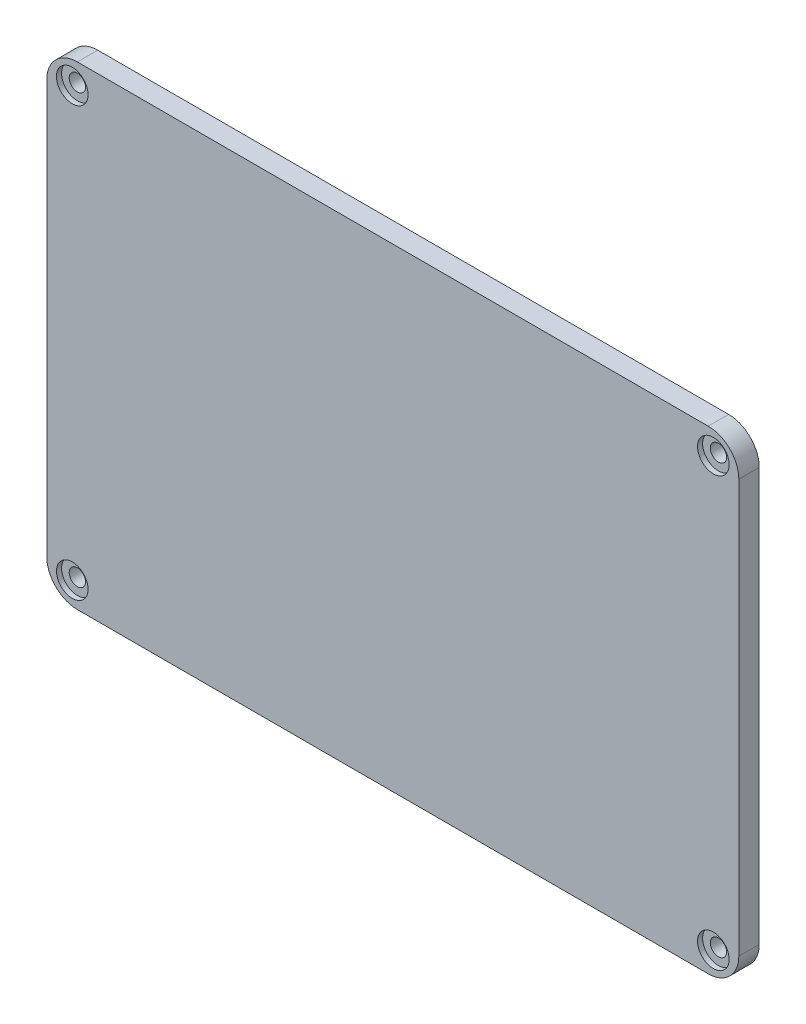
SolidWorks part; units mm, degrees
ref_plane "Front Plane" through (0, 0, 0) normal (0, 0, 1) x (1, 0, 0)
ref_plane "Top Plane" through (0, 0, 0) normal (0, 1, 0) x (1, 0, 0)
ref_plane "Right Plane" through (0, 0, 0) normal (1, 0, 0) x (0, 0, -1)
sketch "Sketch1" plane through (0, 0, 0) normal (0, 0, 1) x (1, 0, 0)
  line L25 (-12.2044, -60.1102) -> (-12.2044, -141.1102)
  line L26 (-6.2044, -147.1102) -> (117.4956, -147.1102)
  line L27 (123.4956, -141.1102) -> (123.4956, -60.1102)
  line L28 (117.4956, -54.1102) -> (-6.2044, -54.1102)
  line L45 (-12.2044, -60.1102) -> (-12.2044, -141.1102)
  line L46 (-6.2044, -147.1102) -> (117.4956, -147.1102)
  line L47 (123.4956, -141.1102) -> (123.4956, -60.1102)
  line L48 (117.4956, -54.1102) -> (-6.2044, -54.1102)
  circle A0 centre (-7.2044, -58.6102) radius 1.6
  circle A1 centre (118.4956, -58.6102) radius 1.6
  circle A2 centre (118.4956, -142.6102) radius 1.6
  circle A3 centre (-7.2044, -142.6102) radius 1.6
  arc A4 (-12.2044, -141.1102) -> (-6.2044, -147.1102) centre (-6.2044, -141.1102) ccw
  arc A5 (117.4956, -147.1102) -> (123.4956, -141.1102) centre (117.4956, -141.1102) ccw
  arc A6 (123.4956, -60.1102) -> (117.4956, -54.1102) centre (117.4956, -60.1102) ccw
  arc A7 (-6.2044, -54.1102) -> (-12.2044, -60.1102) centre (-6.2044, -60.1102) ccw
  arc A8 (-12.2044, -141.1102) -> (-6.2044, -147.1102) centre (-6.2044, -141.1102) ccw
  arc A9 (117.4956, -147.1102) -> (123.4956, -141.1102) centre (117.4956, -141.1102) ccw
  arc A10 (123.4956, -60.1102) -> (117.4956, -54.1102) centre (117.4956, -60.1102) ccw
  arc A11 (-6.2044, -54.1102) -> (-12.2044, -60.1102) centre (-6.2044, -60.1102) ccw
  dimension "D1" = 0
extrude "Boss-Extrude1" add sketch "Sketch1" along normal blind 4
sketch "Sketch2" plane through (0, 0, 4) normal (0, 0, 1) x (1, 0, 0)
  line L0 (55.6456, -54.1102) -> (55.6456, -147.1102) construction
  line L1 (117.4956, -54.1102) -> (-6.2044, -54.1102) construction
  line L2 (-6.2044, -147.1102) -> (117.4956, -147.1102) construction
  line L3 (-12.2044, -100.6102) -> (123.4956, -100.6102) construction
  line L4 (-12.2044, -60.1102) -> (-12.2044, -141.1102) construction
  line L5 (123.4956, -141.1102) -> (123.4956, -60.1102) construction
  circle A0 centre (-7.2044, -58.6102) radius 3.1
  circle A1 centre (118.4956, -58.6102) radius 3.1
  circle A2 centre (118.4956, -142.6102) radius 3.1
  circle A3 centre (-7.2044, -142.6102) radius 3.1
  dimension "D1" = 6.2
extrude "Cut-Extrude1" cut sketch "Sketch2" against normal blind 1
